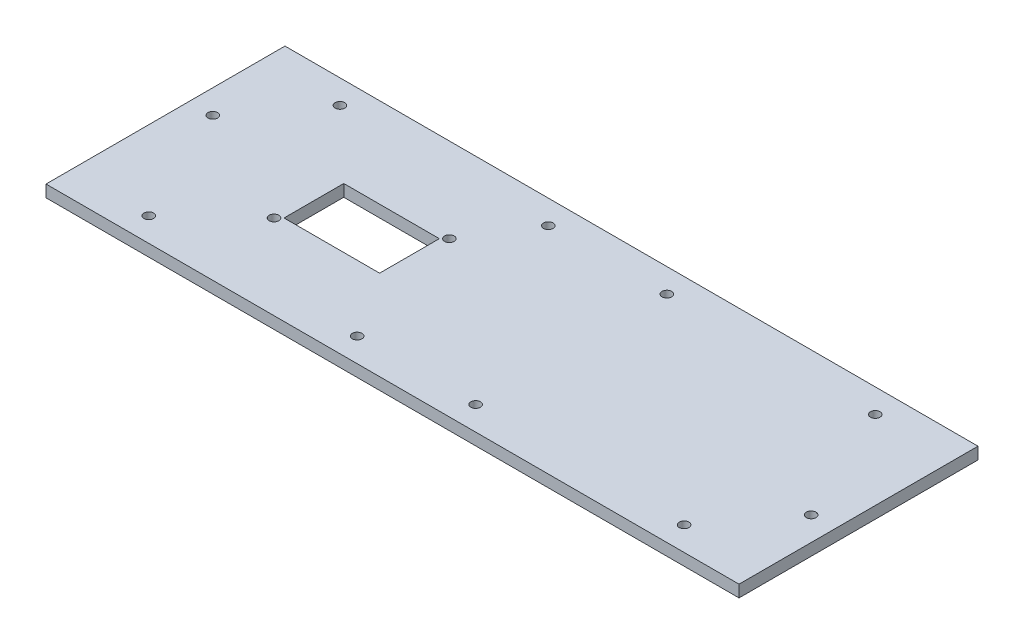
SolidWorks part; units mm, degrees
ref_plane "Front Plane" through (0, 0, 0) normal (0, 0, 1) x (1, 0, 0)
ref_plane "Top Plane" through (0, 0, 0) normal (0, 1, 0) x (1, 0, 0)
ref_plane "Right Plane" through (0, 0, 0) normal (1, 0, 0) x (0, 0, -1)
sketch "Sketch1" plane through (0, 0, 0) normal (0, 1, 0) x (1, 0, 0)
  line L0 (184.15, 0) -> (184.15, 127) construction
  line L1 (368.3, 127) -> (0, 127)
  line L2 (368.3, 127) -> (368.3, 0)
  line L3 (368.3, 0) -> (0, 0)
  line L4 (0, 127) -> (0, 0)
  line L6 (12.7, 114.3) -> (355.6, 114.3) construction
  line L7 (12.7, 114.3) -> (12.7, 12.7) construction
  line L8 (12.7, 12.7) -> (355.6, 12.7) construction
  line L9 (355.6, 114.3) -> (355.6, 12.7) construction
  line L10 (12.7, 114.3) -> (355.6, 12.7) construction
  line L11 (12.7, 12.7) -> (355.6, 114.3) construction
  circle A0 centre (326.39, 12.7) radius 2.5527
  circle A1 centre (41.91, 12.7) radius 2.5527
  circle A2 centre (41.91, 114.3) radius 2.5527
  circle A3 centre (326.39, 114.3) radius 2.5527
  circle A4 centre (215.646, 12.7) radius 2.5527
  circle A5 centre (152.654, 12.7) radius 2.5527
  circle A6 centre (215.646, 114.3) radius 2.5527
  circle A8 centre (152.654, 114.3) radius 2.5527
  circle A9 centre (12.7, 75.946) radius 2.5527
  circle A11 centre (355.6, 51.054) radius 2.5527
  point P7 (184.15, 63.5)
  dimension "D5" = 5.1054
  dimension "D6" = 152.654
  dimension "D7" = 41.91
  dimension "D8" = 5.1054
  dimension "D9" = 152.654
  dimension "D10" = 41.91
  dimension "D11" = 152.654
  dimension "D13" = 5.1054
  dimension "D15" = 5.1054
  dimension "D18" = 5.1054
  dimension "D19" = 152.654
  dimension "D21" = 5.1054
  dimension "D23" = 5.1054
  dimension "D20" = 5.1054
  dimension "D24" = 5.1054
  dimension "D25" = 5.1054
  dimension "D1" = 368.3
  dimension "D2" = 127
  dimension "D3" = 12.7
  dimension "D4" = 12.7
  dimension "D14" = 41.91
  dimension "D16" = 41.91
  dimension "D17" = 51.054
  dimension "D22" = 51.054
extrude "Boss-Extrude1" add sketch "Sketch1" along normal blind 6.35
sketch "Sketch2" plane through (0, 0, 0) normal (0, -1, 0) x (1, 0, 0)
  line L0 (0, -63.5) -> (368.3, -63.5) construction
  line L1 (0, -127) -> (0, 0) construction
  line L2 (368.3, 0) -> (368.3, -127) construction
  line L4 (132.334, -82.042) -> (76.2, -82.042) construction
  line L5 (132.334, -82.042) -> (132.334, -44.958) construction
  line L6 (132.334, -44.958) -> (76.2, -44.958) construction
  line L7 (76.2, -82.042) -> (76.2, -44.958) construction
  line L8 (132.334, -82.042) -> (76.2, -44.958) construction
  line L9 (132.334, -44.958) -> (76.2, -82.042) construction
  line L10 (129.667, -79.375) -> (78.867, -79.375)
  line L11 (129.667, -79.375) -> (129.667, -47.625)
  line L12 (129.667, -47.625) -> (78.867, -47.625)
  line L13 (78.867, -79.375) -> (78.867, -47.625)
  line L14 (129.667, -79.375) -> (78.867, -47.625) construction
  line L15 (129.667, -47.625) -> (78.867, -79.375) construction
  circle A0 centre (76.2, -44.958) radius 2.5527
  circle A1 centre (132.334, -82.042) radius 2.5527
  point P6 (104.267, -63.5)
  point P13 (104.267, -63.5)
  dimension "D4" = 5.1054
  dimension "D5" = 5.1054
  dimension "D1" = 56.134
  dimension "D2" = 37.084
  dimension "D3" = 76.2
  dimension "D6" = 50.8
  dimension "D7" = 31.75
extrude "Cut-Extrude1" cut sketch "Sketch2" against normal up to next
